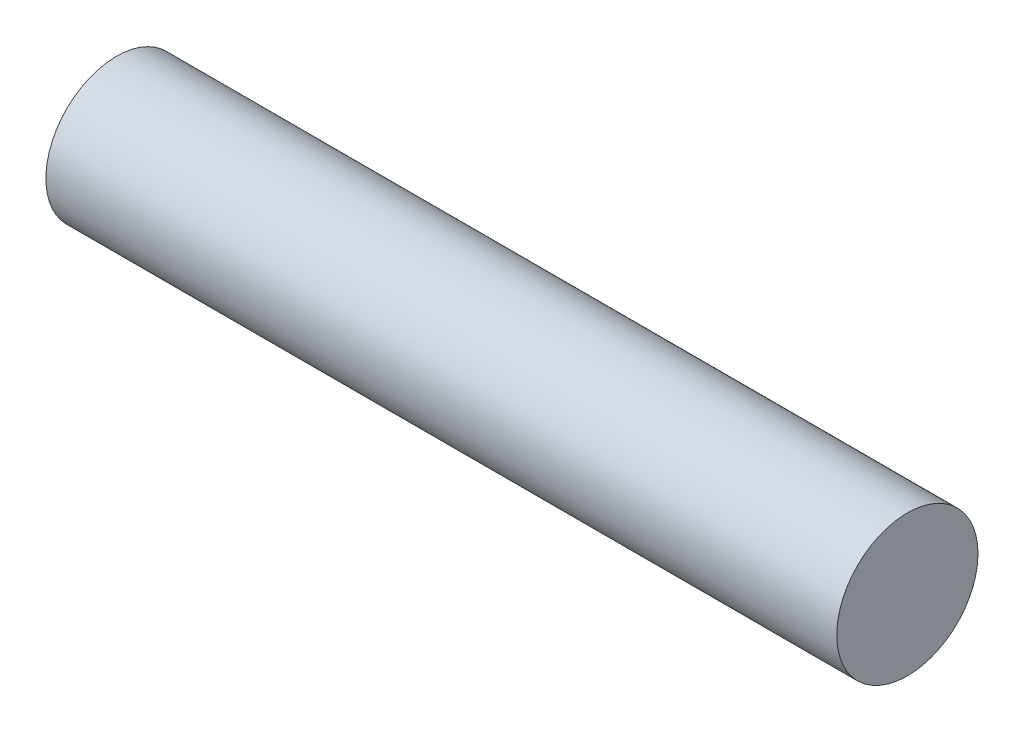
SolidWorks part; units mm, degrees
ref_plane "Front Plane" through (0, 0, 0) normal (0, 0, 1) x (1, 0, 0)
ref_plane "Top Plane" through (0, 0, 0) normal (0, 1, 0) x (1, 0, 0)
ref_plane "Right Plane" through (0, 0, 0) normal (1, 0, 0) x (0, 0, -1)
sketch "Sketch1" plane through (0, 0, 0) normal (1, 0, 0) x (0, 0, -1)
  circle A0 centre (0, 0) radius 2.5
  dimension "D1" = 5
extrude "Boss-Extrude1" add sketch "Sketch1" along normal blind 28
